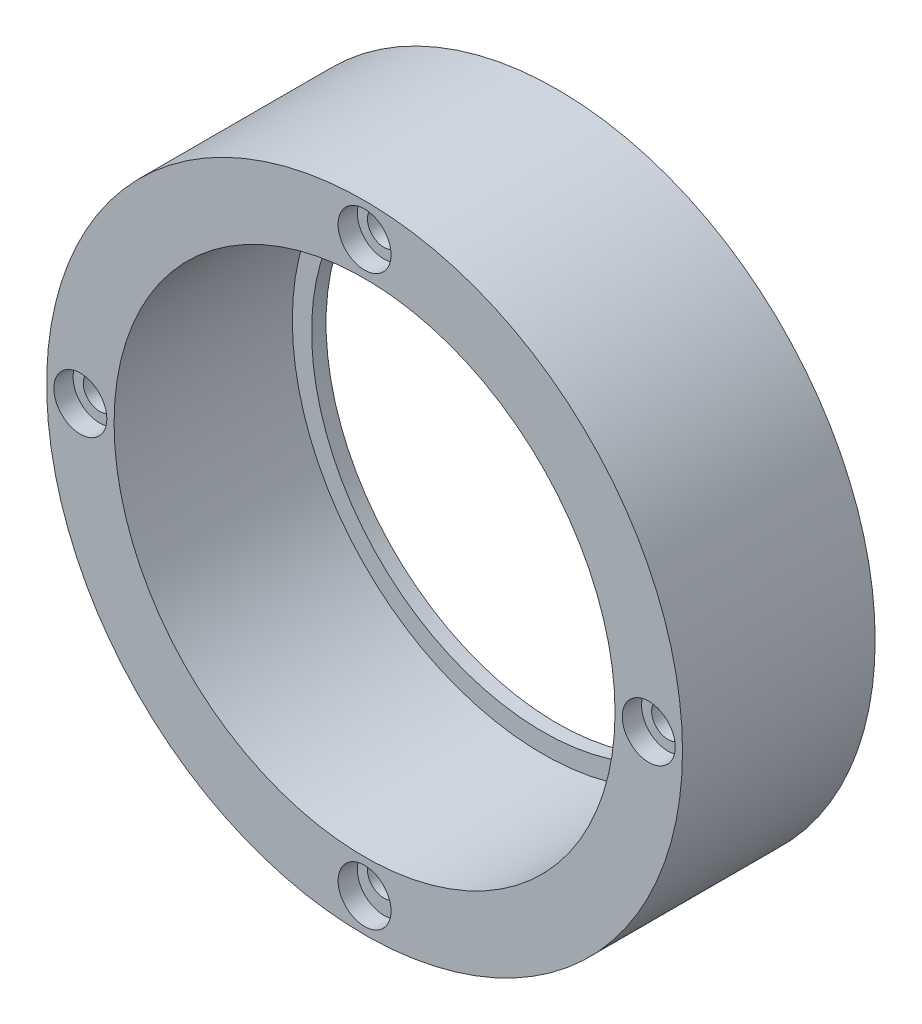
SolidWorks part; units mm, degrees
ref_plane "Front Plane" through (0, 0, 0) normal (0, 0, 1) x (1, 0, 0)
ref_plane "Top Plane" through (0, 0, 0) normal (0, 1, 0) x (1, 0, 0)
ref_plane "Right Plane" through (0, 0, 0) normal (1, 0, 0) x (0, 0, -1)
sketch "Sketch1" plane through (0, 0, 0) normal (0, 0, 1) x (1, 0, 0)
  circle A0 centre (0, 0) radius 33
  circle A1 centre (0, 0) radius 24
  dimension "D1" = 66
  dimension "D2" = 48
extrude "Boss-Extrude1" add sketch "Sketch1" along normal blind 1.5
sketch "Sketch3" plane through (0, 0, 1.5) normal (0, 0, 1) x (1, 0, 0)
  circle A0 centre (0, 0) radius 26
  circle A1 centre (0, 0) radius 33
  dimension "D1" = 52
  dimension "D2" = 66
extrude "Boss-Extrude2" add sketch "Sketch3" along normal blind 18.5
sketch "Sketch4" plane through (0, 0, 20) normal (0, 0, 1) x (1, 0, 0)
  circle A0 centre (0, 29.5) radius 1.7
  circle A1 centre (29.5, 0) radius 1.7
  circle A2 centre (0, -29) radius 1.7
  circle A3 centre (-29.5, 0) radius 1.7
  dimension "D1" = 3.4
  dimension "D2" = 3.4
  dimension "D3" = 3.4
  dimension "D4" = 3.4
  dimension "D5" = 29.5
  dimension "D6" = 29
  dimension "D7" = 29.5
  dimension "D8" = 29.5
extrude "Cut-Extrude1" cut sketch "Sketch4" against normal through all
sketch "Sketch5" plane through (0, 0, 20) normal (0, 0, 1) x (1, 0, 0)
  circle A0 centre (0, 29.5) radius 2.75
  circle A1 centre (29.5, 0) radius 2.75
  circle A2 centre (0, -29.5) radius 2.75
  circle A3 centre (-29.5, 0) radius 2.75
  point P12 (0, 0)
  dimension "D1" = 5.5
  dimension "D2" = 4
extrude "Cut-Extrude2" cut sketch "Sketch5" against normal blind 2
